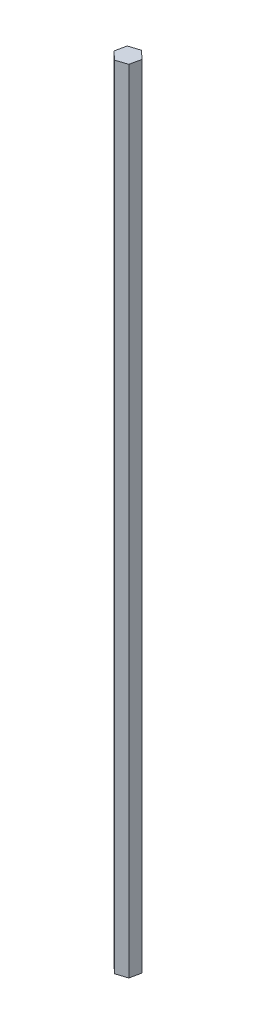
SolidWorks part; units mm, degrees
ref_plane "Front Plane" through (0, 0, 0) normal (0, 0, 1) x (1, 0, 0)
ref_plane "Top Plane" through (0, 0, 0) normal (0, 1, 0) x (1, 0, 0)
ref_plane "Right Plane" through (0, 0, 0) normal (1, 0, 0) x (0, 0, -1)
sketch "Sketch2" plane through (0, 0, 0) normal (0, 1, 0) x (1, 0, 0)
  line L1 (2.1373, -1.9404) -> (2.7491, 0.8807)
  line L2 (2.7491, 0.8807) -> (0.6118, 2.8212)
  line L3 (0.6118, 2.8212) -> (-2.1373, 1.9404)
  line L4 (-2.1373, 1.9404) -> (-2.7491, -0.8807)
  line L5 (-2.7491, -0.8807) -> (-0.6118, -2.8212)
  line L6 (-0.6118, -2.8212) -> (2.1373, -1.9404)
  circle A0 centre (0, 0) radius 2.5 construction
extrude "Boss-Extrude1" add sketch "Sketch2" along normal blind 203.2
